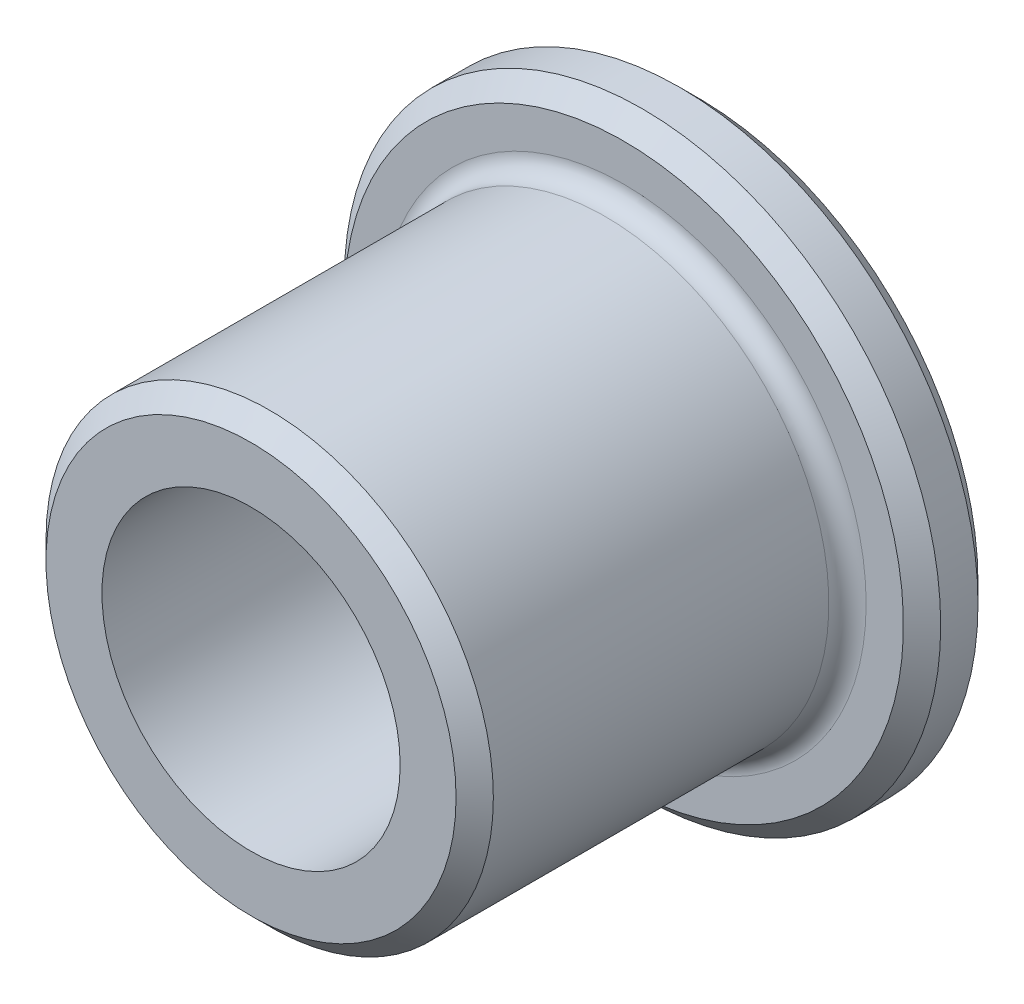
SolidWorks part; units mm, degrees
ref_plane "Plan de face" through (0, 0, 0) normal (0, 0, 1) x (1, 0, 0)
ref_plane "Plan de dessus" through (0, 0, 0) normal (0, 1, 0) x (1, 0, 0)
ref_plane "Plan de droite" through (0, 0, 0) normal (1, 0, 0) x (0, 0, -1)
sketch "Esquisse1" plane through (0, 0, 0) normal (0, 0, 1) x (1, 0, 0)
  circle A0 centre (0, 0) radius 6
extrude "Extrusion1" add sketch "Esquisse1" along normal blind 12
sketch "Esquisse2" plane through (0, 0, 12) normal (0, 0, 1) x (1, 0, 0)
  circle A0 centre (0, 0) radius 4
extrude "Extrusion2" cut sketch "Esquisse2" against normal through all
sketch "Esquisse3" plane through (0, 0, 0) normal (0, 1, 0) x (1, 0, 0)
  line L1 (4, 0) -> (-4, 0) construction
  line L2 (4, 0) -> (8, 0)
  line L3 (4, 0) -> (4, -2)
  line L4 (4, -2) -> (8, -2)
  line L5 (8, 0) -> (8, -2)
  line L6 (0, 1.4564) -> (0, -3.034)
  dimension "D1" = 4
  dimension "D2" = 8
  dimension "D3" = 2
revolve "Révolution2" add sketch "Esquisse3" angle 360 about L6
chamfer "Chanfrein1" distance 0.5 angle 45 3 edges at (-8, 0, 2) (-8, 0, 0) (6, 0, 12)
fillet "Congé1" radius 0.5 1 edges at (-6, 0, 2)
